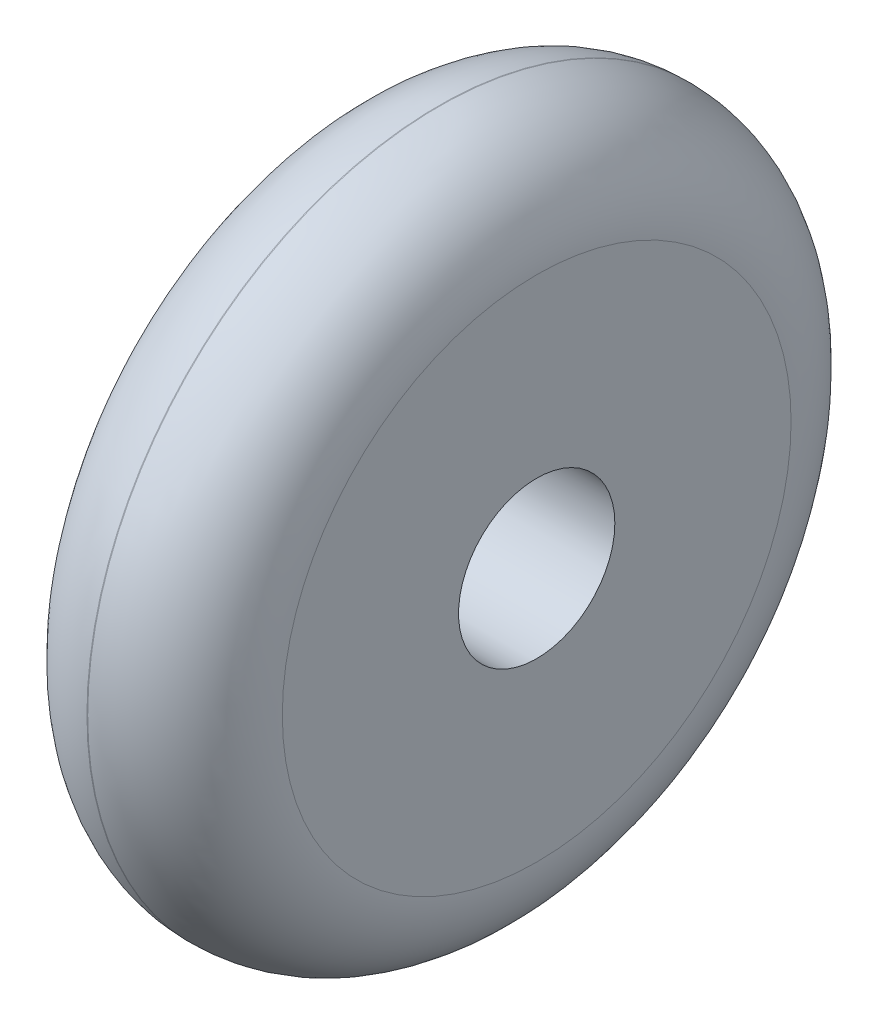
SolidWorks part; units mm, degrees
ref_plane "Front Plane" through (0, 0, 0) normal (0, 0, 1) x (1, 0, 0)
ref_plane "Top Plane" through (0, 0, 0) normal (0, 1, 0) x (1, 0, 0)
ref_plane "Right Plane" through (0, 0, 0) normal (1, 0, 0) x (0, 0, -1)
sketch "Sketch2" plane through (0, 0, 0) normal (1, 0, 0) x (0, 0, -1)
  circle A0 centre (0, 0) radius 9
  circle A1 centre (0, 0) radius 2
  dimension "D1" = 18
  dimension "D2" = 4
extrude "Boss-Extrude1" add sketch "Sketch2" along normal blind 5
fillet "Fillet1" radius 2.49 2 edges at (0, 0, -9) (5, 0, -9)
ref_plane "Plane1" through (2.5, 0, 0) normal (1, 0, 0) x (0, 0, -1)
